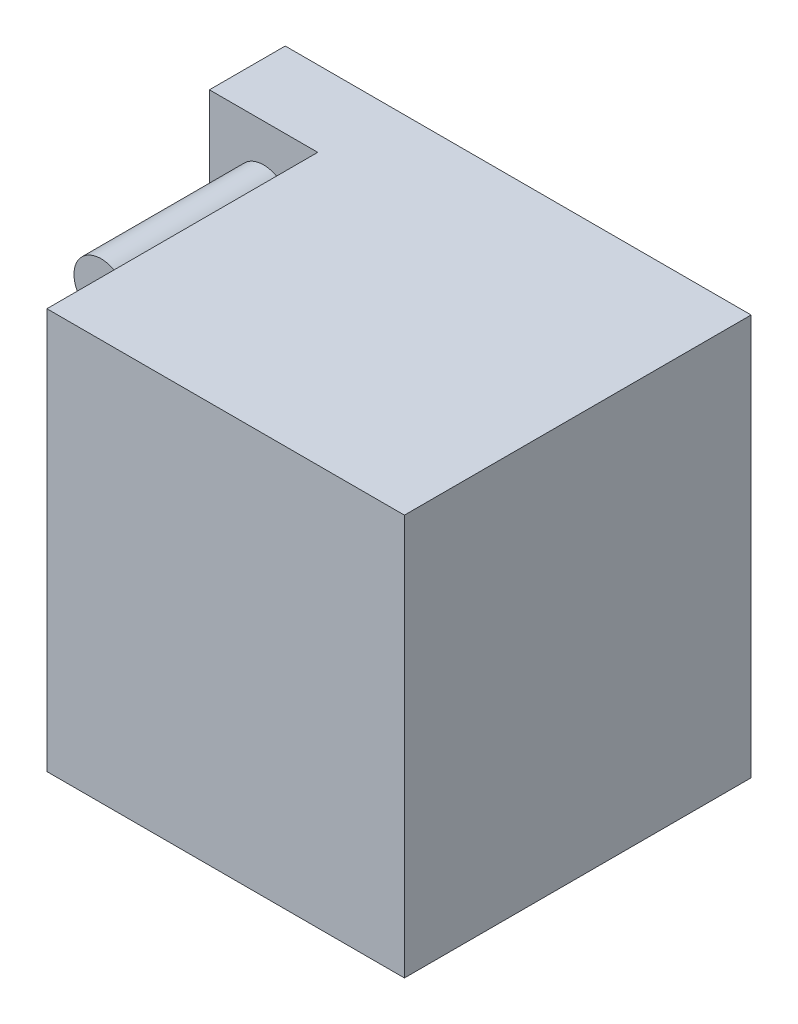
SolidWorks part; units mm, degrees
material "ABS"
ref_plane "Front" through (0, 0, 0) normal (0, 0, 1) x (1, 0, 0)
ref_plane "Top" through (0, 0, 0) normal (0, 1, 0) x (1, 0, 0)
ref_plane "Right" through (0, 0, 0) normal (1, 0, 0) x (0, 0, -1)
sketch "Sketch1" plane through (0, 0, 0) normal (0, 0, 1) x (1, 0, 0)
  line L1 (0, 0) -> (43, 0)
  line L2 (0, 0) -> (0, -37)
  line L3 (0, -37) -> (43, -37)
  line L4 (43, 0) -> (43, -37)
  dimension "D1" = 43
  dimension "D2" = 37
extrude "Boss-Extrude1" add sketch "Sketch1" along normal blind 32
sketch "Sketch2" plane through (0, 0, 32) normal (0, 0, 1) x (1, 0, 0)
  line L0 (0, -37) -> (43, -37) construction
  line L1 (0, 0) -> (10, 0)
  line L2 (0, 0) -> (0, -37)
  line L3 (0, -37) -> (10, -37)
  line L4 (10, 0) -> (10, -37)
  dimension "D1" = 10
extrude "Cut-Extrude1" cut sketch "Sketch2" against normal blind 25
sketch "Sketch3" plane through (0, 0, 7) normal (0, 0, 1) x (1, 0, 0)
  line L0 (10, 0) -> (0, 0) construction
  circle A0 centre (5, -6) radius 2.5
  circle A1 centre (5, -14) radius 2.5
  circle A2 centre (5, -22) radius 2.5
  circle A3 centre (5, -30) radius 2.5
  dimension "D1" = 5
  dimension "D2" = 6
  dimension "D3" = 4
extrude "Boss-Extrude2" add sketch "Sketch3" along normal blind 15
